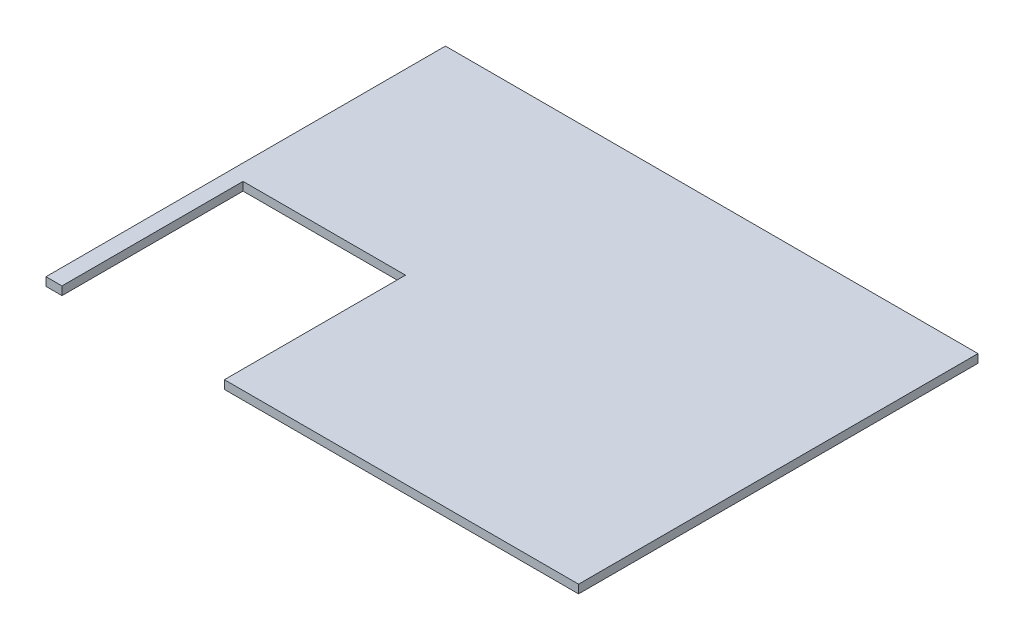
SolidWorks part; units mm, degrees
ref_plane "Front Plane" through (0, 0, 0) normal (0, 0, 1) x (1, 0, 0)
ref_plane "Top Plane" through (0, 0, 0) normal (0, 1, 0) x (1, 0, 0)
ref_plane "Right Plane" through (0, 0, 0) normal (1, 0, 0) x (0, 0, -1)
sketch "Sketch1" plane through (0, 0, 0) normal (0, 1, 0) x (1, 0, 0)
  line L0 (3, 0) -> (3, 75) construction
  line L1 (33.5, 0) -> (33.5, 75) construction
  line L2 (0, 34) -> (100, 34) construction
  line L3 (0, 0) -> (3, 0)
  line L4 (3, 0) -> (3, 34)
  line L5 (0, 75) -> (100, 75) construction
  line L6 (0, 75) -> (0, 0) construction
  line L7 (0, 0) -> (100, 0) construction
  line L8 (100, 75) -> (100, 0) construction
  line L9 (3, 34) -> (33.5, 34)
  line L10 (33.5, 34) -> (33.5, 0)
  line L11 (33.5, 0) -> (100, 0)
  line L12 (100, 0) -> (100, 75)
  line L13 (100, 75) -> (0, 75)
  line L14 (0, 75) -> (0, 0)
extrude "Boss-Extrude1" add sketch "Sketch1" along normal blind 1.5875
